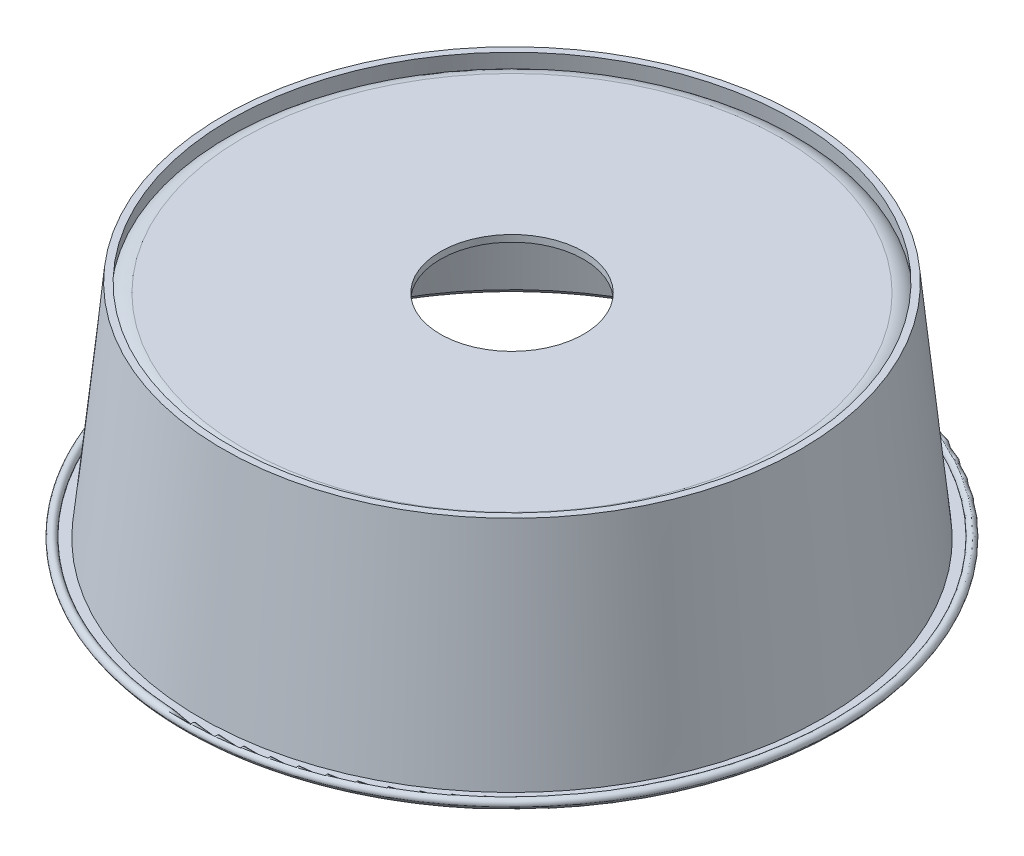
SolidWorks part; units mm, degrees
material "PE High Density"
ref_plane "Front Plane" through (0, 0, 0) normal (0, 0, 1) x (1, 0, 0)
ref_plane "Top Plane" through (0, 0, 0) normal (0, 1, 0) x (1, 0, 0)
ref_plane "Right Plane" through (0, 0, 0) normal (1, 0, 0) x (0, 0, -1)
sketch "Sketch1" plane through (0, 0, 0) normal (0, 0, 1) x (1, 0, 0)
  line L0 (0, 0) -> (0, 132) construction
  line L1 (0, 0) -> (187.3679, 0) construction
  line L2 (86.7, 68.7) -> (93.4603, 2.2)
  line L3 (86.7, 95.2587) -> (86.7, 0) construction
  line L4 (86.7, 68.7) -> (84.6897, 68.7)
  line L5 (84.6897, 68.7) -> (85.1696, 63.9795)
  line L6 (80.6897, 66) -> (0, 66)
  line L7 (0, 64) -> (80.6897, 64)
  line L8 (85.5741, 60) -> (91.45, 2.2)
  line L9 (93.4603, 2.2) -> (96.45, 2.2)
  line L10 (95.052, 0) -> (95.552, 0)
  line L11 (0, 64) -> (0, 66)
  line L12 (84.0851, 94.422) -> (93.684, 0) construction
  line L13 (82.6865, 88.405) -> (91.6736, 0) construction
  arc A0 (80.6897, 66) -> (85.1696, 63.9795) centre (80.1946, 58.9256) cw
  arc A1 (80.6897, 64) -> (85.5741, 60) centre (79.1084, 57.0869) cw
  arc A2 (95.052, 0) -> (91.45, 2.2) centre (95.139, 4.1911) cw
  arc A3 (96.45, 2.2) -> (98.85, 2.2) centre (97.65, 2.6265) cw
  arc A4 (95.552, 0) -> (98.85, 2.2) centre (95.139, 4.1911) ccw
  dimension "D5" = 2
  dimension "D2" = 1.7
  dimension "D13" = 98.85
  dimension "D3" = 2.4
  dimension "D4" = 7.4
  dimension "D6" = 0
  dimension "D7" = 0.5
  dimension "D8" = 3.9
  dimension "D9" = 4
  dimension "D10" = 2.7
  dimension "D11" = 4
  dimension "D12" = 2
  dimension "D14" = 2
  dimension "D15" = 86.7
  dimension "D16" = 64
  dimension "D17" = 4
  dimension "D18" = 5.805
  dimension "D19" = 85.1696
  dimension "D20" = 91.6736
revolve "Chassi Revolve1" add sketch "Sketch1" angle 360 about L0
sketch "Sketch2" plane through (0, 66, 0) normal (0, 1, 0) x (1, 0, 0)
  circle A0 centre (0, 0) radius 21.5
  dimension "D1" = 43
extrude "Distance Hole Cut-Extrude1" cut sketch "Sketch2" against normal up to surface (2 mm away) up to face at (80.6897, 64, 0)
